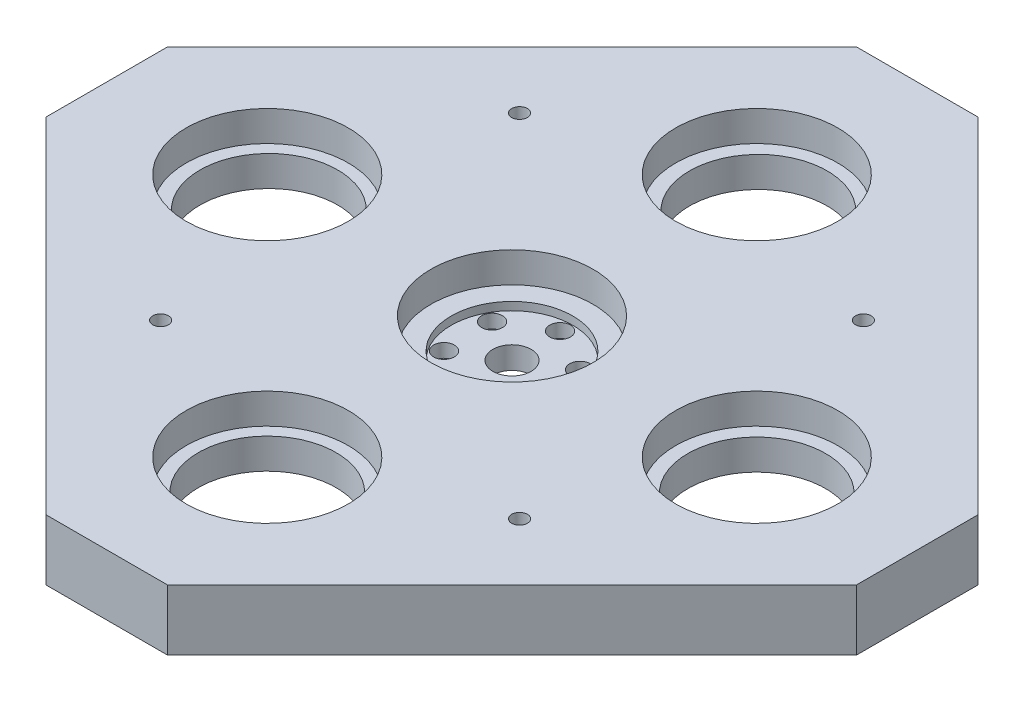
SolidWorks part; units mm, degrees
material "Pine"
ref_plane "Front Plane" through (0, 0, 0) normal (0, 0, 1) x (1, 0, 0)
ref_plane "Top Plane" through (0, 0, 0) normal (0, 1, 0) x (1, 0, 0)
ref_plane "Right Plane" through (0, 0, 0) normal (1, 0, 0) x (0, 0, -1)
sketch "Sketch1" plane through (0, 0, 0) normal (0, 1, 0) x (1, 0, 0)
  line L1 (0, 0) -> (254, 0)
  line L2 (0, 0) -> (0, 254)
  line L3 (0, 254) -> (254, 254)
  line L4 (254, 0) -> (254, 254)
  dimension "D1" = 254
  dimension "D2" = 254
extrude "Boss-Extrude1" add sketch "Sketch1" along normal blind 19.05
sketch "Sketch2" plane through (0, 19.05, 0) normal (0, 1, 0) x (1, 0, 0)
  line L0 (0, 0) -> (254, 0) construction
  circle A1 centre (127, 50.292) radius 25.4
  circle A4 centre (50.292, 127) radius 25.4
  circle A5 centre (127, 127) radius 25.4
  circle A6 centre (127, 203.708) radius 25.4
  circle A7 centre (127, 127) radius 25.4
  circle A8 centre (203.708, 127) radius 25.4
  circle A9 centre (127, 127) radius 25.4
  point P18 (127, 127)
  dimension "D2" = 50.8
  dimension "D5" = 4
  dimension "D3" = 76.708
  dimension "D4" = 127
extrude "Cut-Extrude1" cut sketch "Sketch2" against normal blind 9.525 contours A4 | A1 | A5 | A8 | A6
sketch "Sketch3" plane through (0, 9.525, 0) normal (0, 1, 0) x (1, 0, 0)
  circle A0 centre (127, 127) radius 6
  dimension "D1" = 12
extrude "Cut-Extrude2" cut sketch "Sketch3" against normal through all
hole_wizard "CBORE for M3 SHCS1" positions "Sketch4" profile "Sketch5" counterbore size "M3" standard "ANSI Metric"
sketch "Sketch4" plane through (0, 9.525, 0) normal (0, 1, 0) x (1, 0, 0)
  circle A0 centre (127, 127) radius 6 construction
  point P0 (127.4249, 111.5058)
  point P11 (113.7941, 118.885)
  point P12 (113.3692, 134.3791)
  point P13 (126.5751, 142.4942)
  point P16 (140.2059, 135.115)
  point P17 (140.6308, 119.6209)
  dimension "D1" = 15.5
  dimension "D2" = 6
sketch "Sketch5" plane through (127.4249, 9.525, -111.5058) normal (1, 0, 0) x (0, 0, 1)
  line L0 (0, 0) -> (0, 11.6895)
  line L1 (0, 11.6895) -> (1.7, 10.668)
  line L2 (1.7, 10.668) -> (1.7, 6.81)
  line L3 (1.7, 6.81) -> (3.25, 6.81)
  line L5 (3.25, 6.81) -> (3.25, 0.025)
  line L6 (3.25, 0.025) -> (3.275, 0)
  line L7 (3.275, 0) -> (0, 0)
  line L8 (-3.25, 0.025) -> (-3.275, 0) construction
  line L10 (0, 11.6895) -> (-1.7, 10.668) construction
  line L11 (0, -6.35) -> (0, 107.95) construction
  dimension "Hole Dia." = 3.4
  dimension "Hole Depth" = 10.668
  dimension "C'Bore Dia." = 6.5
  dimension "C'Bore Depth" = 6.81
  dimension "Near C'Sink Dia." = 6.55
  dimension "Near C'Sink Angle" = 90
  dimension "Drill Angle" = 118
sketch "Sketch6" plane through (0, 9.525, 0) normal (0, 1, 0) x (1, 0, 0)
  circle A0 centre (127, 50.292) radius 19.05
  circle A1 centre (50.546, 127.254) radius 19.05
  circle A2 centre (127.508, 203.708) radius 19.05
  circle A3 centre (203.962, 126.746) radius 19.05
  point P12 (127.254, 127)
  dimension "D1" = 4
  dimension "D2" = 76.708
extrude "Cut-Extrude3" cut sketch "Sketch6" against normal blind 2.54
sketch "Sketch7" plane through (0, 9.525, 0) normal (0, 1, 0) x (1, 0, 0)
  circle A0 centre (127, 127) radius 19.05
  dimension "D1" = 38.1
extrude "Cut-Extrude4" cut sketch "Sketch7" against normal blind 2.54
fillet "Fillet1" radius 107.95 4 edges at (0, 9.525, -254) (0, 9.525, 0) (254, 9.525, 0) (254, 9.525, -254) profile chamfer
hole_wizard "CSK for #8 Flat Head Machine Screw (100)2" positions "Sketch11" profile "Sketch12" countersink size "#8" standard "ANSI Inch" end condition through all
sketch "Sketch11" plane through (0, 0, 0) normal (0, -1, 0) x (-1, 0, 0)
  line L0 (-107.95, 0) -> (0, 107.95) construction
  line L1 (-254, 107.95) -> (-146.05, 0) construction
  line L2 (0, 146.05) -> (-107.95, 254) construction
  line L3 (-146.05, 254) -> (-254, 146.05) construction
  point P0 (-183.2474, 73.1185)
  point P2 (-73.1185, 70.7526)
  point P4 (-183.2474, 180.8815)
  point P6 (-73.1185, 183.2474)
  dimension "D1" = 101.6
  dimension "D2" = 25.4
  dimension "D3" = 25.4
  dimension "D4" = 25.4
  dimension "D5" = 101.6
  dimension "D6" = 101.6
  dimension "D7" = 101.6
  dimension "D8" = 25.4
sketch "Sketch12" plane through (183.2474, 0, -73.1185) normal (1, 0, 0) x (0, 0, -1)
  line L0 (0, 0) -> (0, 19.05)
  line L1 (0, 19.05) -> (2.4574, 19.05)
  line L2 (2.4574, 19.05) -> (2.4574, 1.4759)
  line L3 (2.4574, 1.4759) -> (4.2164, 0)
  line L5 (4.2164, 0) -> (0, 0)
  line L6 (-2.4574, 1.4759) -> (-4.2164, 0) construction
  line L11 (0, -6.35) -> (0, 107.95) construction
  dimension "Thru Hole Dia." = 4.9149
  dimension "Thru Hole Depth" = 19.05
  dimension "Near C'Sink Dia." = 8.4328
  dimension "Near C'Sink Angle" = 100
sketch "Sketch14" plane through (0, 6.985, 0) normal (0, 1, 0) x (1, 0, 0)
  circle A0 centre (127, 50.292) radius 21.59
  circle A1 centre (203.962, 126.746) radius 21.59
  circle A2 centre (127.508, 203.708) radius 21.59
  circle A3 centre (50.546, 127.254) radius 21.59
  dimension "D1" = 43.18
extrude "Cut-Extrude6" cut sketch "Sketch14" against normal through all both and the other way through all
